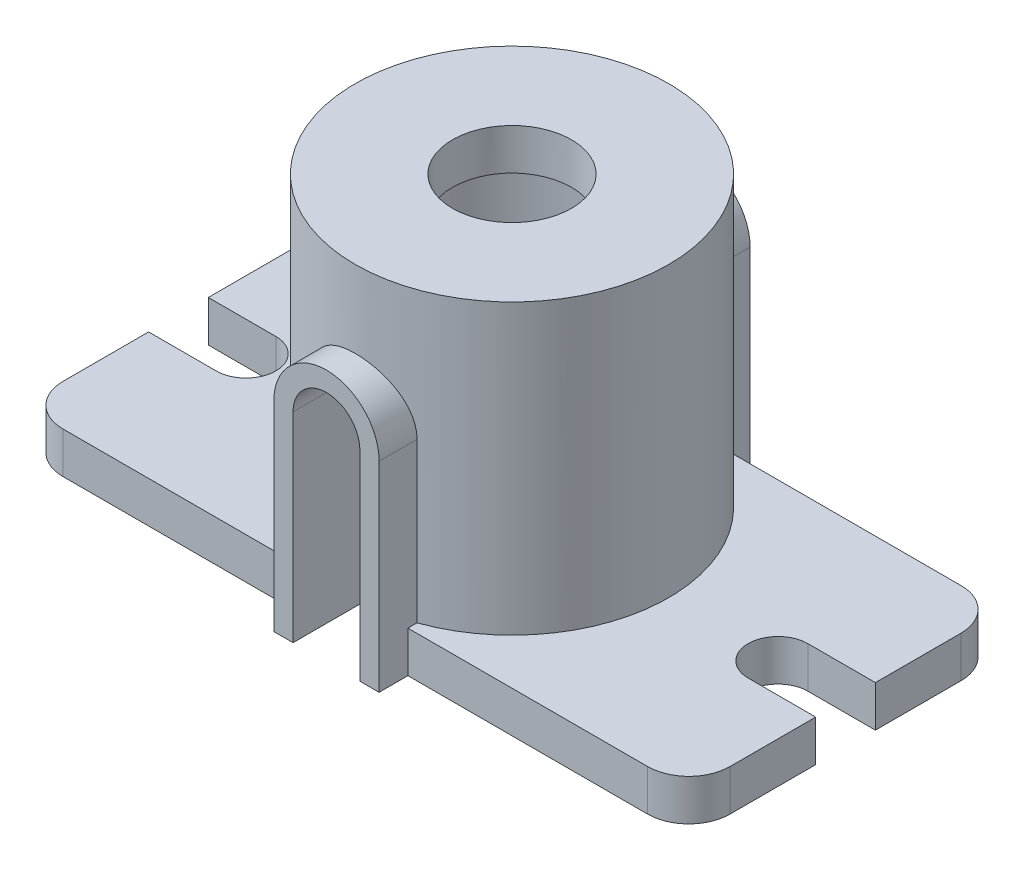
SolidWorks part; units mm, degrees
ref_plane "前视基准面" through (0, 0, 0) normal (0, 0, 1) x (1, 0, 0)
ref_plane "上视基准面" through (0, 0, 0) normal (0, 1, 0) x (1, 0, 0)
ref_plane "右视基准面" through (0, 0, 0) normal (1, 0, 0) x (0, 0, -1)
sketch "草图1" plane through (0, 0, 0) normal (0, 1, 0) x (1, 0, 0)
  line L1 (-80.9079, -38.0141) -> (80.9079, -38.0141)
  line L2 (-80.9079, -38.0141) -> (-80.9079, 38.0141)
  line L3 (-80.9079, 38.0141) -> (80.9079, 38.0141)
  line L4 (80.9079, -38.0141) -> (80.9079, 38.0141)
  line L5 (-80.9079, -38.0141) -> (80.9079, 38.0141) construction
  line L6 (-80.9079, 38.0141) -> (80.9079, -38.0141) construction
  point P0 (0, 0)
extrude "凸台-拉伸1" add sketch "草图1" along normal blind 10
fillet "圆角1" radius 10 4 edges at (80.9079, 5, -38.0141) (-80.9079, 5, -38.0141) (80.9079, 5, 38.0141) (-80.9079, 5, 38.0141)
sketch "草图4" plane through (0, 0, 0) normal (0, 1, 0) x (1, 0, 0)
  line L0 (-97.2921, 0) -> (-64.5238, 0) construction
  line L1 (-80.9079, 28.0141) -> (-80.9079, -28.0141) construction
  line L2 (-80.9079, 7.2425) -> (-64.5238, 7.2425)
  line L3 (-80.9079, -7.2425) -> (-64.5238, -7.2425)
  line L4 (-80.9079, 7.2425) -> (-80.9079, -7.2425)
  arc A1 (-64.5238, -7.2425) -> (-64.5238, 7.2425) centre (-64.5238, 0) ccw
  point P5 (-80.9079, 0)
extrude "切除-拉伸5" cut sketch "草图4" along normal blind 27 contours L2 A1 L3 L4
mirror "镜向7" about plane through (0, 0, 0) normal (1, 0, 0) of "切除-拉伸5"
sketch "草图5" plane through (0, 0, 0) normal (0, 1, 0) x (1, 0, 0)
  circle A0 centre (0, 0) radius 38.0141
extrude "凸台-拉伸2" add sketch "草图5" along normal blind 80
sketch "草图6" plane through (0, 0, 0) normal (0, 0, 1) x (1, 0, 0)
  line L0 (0, -48.5593) -> (0, 48.5593) construction
  line L1 (-12.7629, 0) -> (-12.7629, 48.5593)
  line L2 (12.7629, 0) -> (12.7629, 48.5593)
  line L3 (-12.7629, 0) -> (12.7629, 0)
  arc A1 (12.7629, 48.5593) -> (-12.7629, 48.5593) centre (0, 48.5593) ccw
  point P2 (0, 0)
extrude "凸台-拉伸4" add sketch "草图6" along normal blind 45 and the other way blind 45 contours L1 A1 L2 L3
sketch "草图9" plane through (0, 0, 45) normal (0, 0, 1) x (1, 0, 0)
  line L0 (0, 0) -> (0, 48.5018) construction
  line L1 (-8.1035, 0) -> (-8.1035, 48.5018)
  line L2 (8.1035, 0) -> (8.1035, 48.5018)
  line L3 (-8.1035, 0) -> (8.1035, 0)
  arc A1 (8.1035, 48.5018) -> (-8.1035, 48.5018) centre (0, 48.5018) ccw
  point P2 (0, 0)
extrude "切除-拉伸6" cut sketch "草图9" against normal blind 119
sketch "草图11" plane through (0, 0, 0) normal (0, -1, 0) x (1, 0, 0)
  circle A0 centre (0, 0) radius 28.2636
extrude "切除-拉伸8" cut sketch "草图11" against normal blind 70
sketch "草图12" plane through (0, 80, 0) normal (0, 1, 0) x (1, 0, 0)
  circle A0 centre (0, 0) radius 14.4314
extrude "切除-拉伸9" cut sketch "草图12" against normal blind 70
